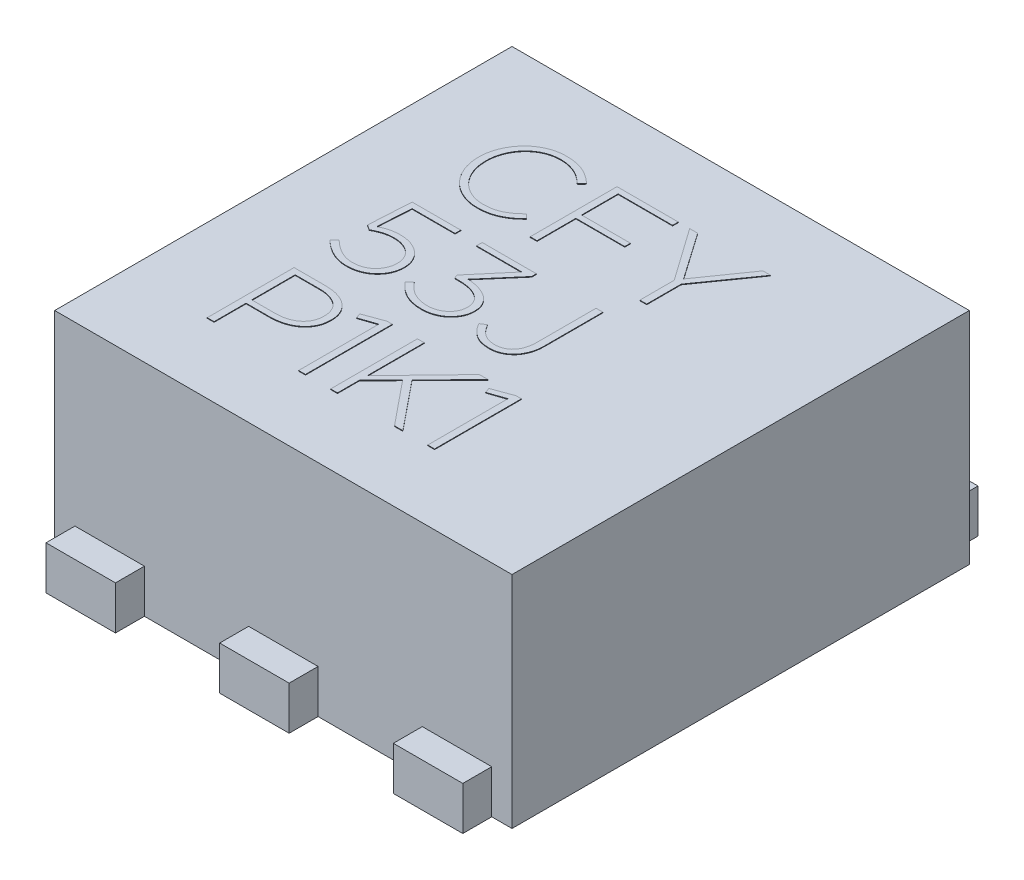
SolidWorks part; units mm, degrees
ref_plane "Front Plane" through (0, 0, 0) normal (0, 0, 1) x (1, 0, 0)
ref_plane "Top Plane" through (0, 0, 0) normal (0, 1, 0) x (1, 0, 0)
ref_plane "Right Plane" through (0, 0, 0) normal (1, 0, 0) x (0, 0, -1)
sketch "Sketch1" plane through (0, 0, 0) normal (0, 1, 0) x (1, 0, 0)
  line L1 (-1.0033, 1.0033) -> (1.0033, 1.0033)
  line L2 (-1.0033, 1.0033) -> (-1.0033, -1.0033)
  line L3 (-1.0033, -1.0033) -> (1.0033, -1.0033)
  line L4 (1.0033, 1.0033) -> (1.0033, -1.0033)
  line L5 (-1.0033, 1.0033) -> (1.0033, -1.0033) construction
  line L6 (-1.0033, -1.0033) -> (1.0033, 1.0033) construction
  point P0 (0, 0)
  dimension "D1" = 2.0066
extrude "Boss-Extrude1" add sketch "Sketch1" along normal blind 0.9652
sketch "Sketch2" plane through (0, 0, 1.0033) normal (0, 0, 1) x (1, 0, 0)
  line L0 (-1.0033, 0) -> (1.0033, 0) construction
  line L1 (-0.1524, 0) -> (0.1524, 0)
  line L2 (-0.1524, 0) -> (-0.1524, 0.1905)
  line L3 (-0.1524, 0.1905) -> (0.1524, 0.1905)
  line L4 (0.1524, 0) -> (0.1524, 0.1905)
  line L5 (-0.1524, 0.1905) -> (-0.6096, 0.1905) construction
  line L6 (0.6096, 0) -> (0.9144, 0)
  line L7 (0.6096, 0) -> (0.6096, 0.1905)
  line L8 (0.6096, 0.1905) -> (0.9144, 0.1905)
  line L9 (0.9144, 0) -> (0.9144, 0.1905)
  line L10 (-0.6096, 0) -> (-0.9144, 0)
  line L11 (-0.6096, 0) -> (-0.6096, 0.1905)
  line L12 (-0.6096, 0.1905) -> (-0.9144, 0.1905)
  line L13 (-0.9144, 0) -> (-0.9144, 0.1905)
  line L14 (0.6096, 0.1905) -> (0.1524, 0.1905) construction
  point P15 (0, 0)
  point P16 (0, 0)
  dimension "D1" = 0.3048
  dimension "D2" = 0.4572
  dimension "D3" = 0.1905
extrude "Boss-Extrude2" add sketch "Sketch2" along normal blind 0.127
mirror "Mirror1" about plane through (0, 0, 0) normal (0, 0, 1) of "Boss-Extrude2"
sketch "Sketch3" plane through (0, 0.9652, 0) normal (0, 1, 0) x (1, 0, 0)
  line L0 (-0.6939, 0.3175) -> (0.8448, 0.3175) construction
  line L1 (-0.6939, -0.1905) -> (0.4857, -0.1905) construction
  line L2 (-0.6939, -0.6985) -> (0.787, -0.6985) construction
  text T0 "CFY" font "Gotham Light" height 0.381
  text T1 "53J" font "Gotham Light" height 0.381
  text T2 "P1K1" font "Gotham Light" height 0.381
  point P5 (-0.8811, 0.4477)
  point P8 (0.8448, 0.44)
  point P9 (0, 0)
  point P10 (0.4857, -0.1529)
  point P11 (0.787, -0.7911)
  point P12 (-0.6939, -0.7949)
  point P13 (-0.0215, -0.0887)
  dimension "D1" = 0.508
  dimension "D2" = 0.508
  dimension "D3" = 0.1905
extrude "Boss-Extrude3" add sketch "Sketch3" along normal blind 0.0025
equation "\"D2@Sketch2\"=\"D1@Sketch2\"*1.5"
